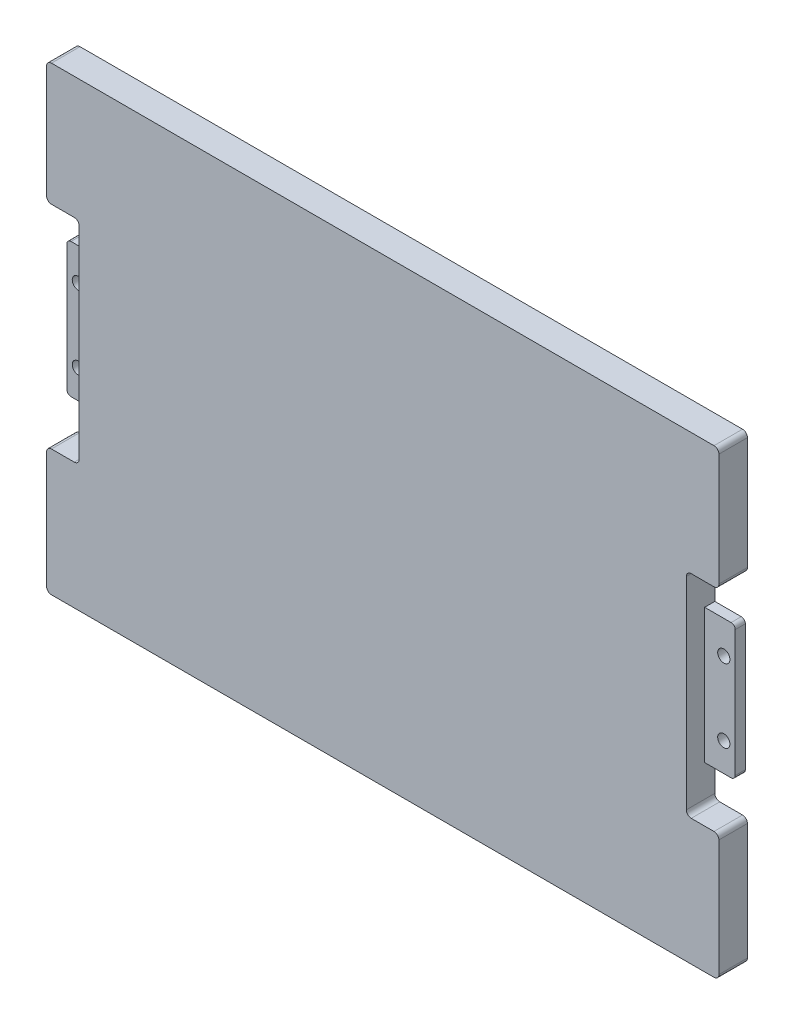
SolidWorks part; units mm, degrees
material "PBTP"
ref_plane "Front" through (0, 0, 0) normal (0, 0, 1) x (1, 0, 0)
ref_plane "Top" through (0, 0, 0) normal (0, 1, 0) x (1, 0, 0)
ref_plane "Right" through (0, 0, 0) normal (1, 0, 0) x (0, 0, -1)
sketch "Эскиз1" plane through (0, 0, 0) normal (0, 0, 1) x (1, 0, 0)
  line L0 (1.2018, 83) -> (6.7982, 83)
  line L1 (1.2018, 0) -> (163.7982, 0)
  line L2 (0, 1.2018) -> (0, 29.7982)
  line L3 (1.2018, 113) -> (163.7982, 113)
  line L4 (165, 1.2018) -> (165, 29.7982)
  line L5 (8, 81.7982) -> (8, 32.2018)
  line L6 (6.7982, 31) -> (1.2018, 31)
  line L7 (0, 84.2018) -> (0, 111.7982)
  line L8 (158.2018, 83) -> (163.7982, 83)
  line L9 (158.2018, 31) -> (163.7982, 31)
  line L10 (157, 81.7982) -> (157, 32.2018)
  line L11 (165, 84.2018) -> (165, 111.7982)
  arc A0 (0, 111.7982) -> (1.2018, 113) centre (1.2018, 111.7982) cw
  arc A1 (6.7982, 83) -> (8, 81.7982) centre (6.7982, 81.7982) cw
  arc A2 (1.2018, 83) -> (0, 84.2018) centre (1.2018, 84.2018) cw
  arc A3 (8, 32.2018) -> (6.7982, 31) centre (6.7982, 32.2018) cw
  arc A4 (1.2018, 31) -> (0, 29.7982) centre (1.2018, 29.7982) ccw
  arc A5 (1.2018, 0) -> (0, 1.2018) centre (1.2018, 1.2018) cw
  arc A6 (163.7982, 0) -> (165, 1.2018) centre (163.7982, 1.2018) ccw
  arc A7 (157, 32.2018) -> (158.2018, 31) centre (158.2018, 32.2018) ccw
  arc A8 (163.7982, 31) -> (165, 29.7982) centre (163.7982, 29.7982) cw
  arc A9 (158.2018, 83) -> (157, 81.7982) centre (158.2018, 81.7982) ccw
  arc A10 (163.7982, 83) -> (165, 84.2018) centre (163.7982, 84.2018) ccw
  arc A11 (163.7982, 113) -> (165, 111.7982) centre (163.7982, 111.7982) cw
  point P15 (0, 113)
  point P18 (8, 83)
  point P21 (0, 83)
  point P24 (8, 31)
  point P29 (0, 0)
  point P32 (165, 0)
  point P41 (165, 83)
  dimension "D9" = 1.2018
  dimension "D1" = 113
  dimension "D2" = 165
  dimension "D3" = 30
  dimension "D4" = 31
  dimension "D5" = 8
  dimension "D6" = 8
  dimension "D7" = 30
  dimension "D8" = 31
extrude "Бобышка-Вытянуть1" add sketch "Эскиз1" along normal blind 7
sketch "Эскиз2" plane through (0, 0, 0) normal (0, 0, -1) x (-1, 0, 0)
  line L0 (-163.7982, 113) -> (-1.2018, 113) construction
  line L1 (-161.7982, 111) -> (-3.2018, 111)
  line L2 (-163, 109.7982) -> (-163, 86.2018)
  line L3 (-161.7982, 2) -> (-3.2018, 2)
  line L4 (-2, 109.7982) -> (-2, 86.2018)
  line L5 (-1.2018, 0) -> (-163.7982, 0) construction
  line L6 (-165, 1.2018) -> (-165, 29.7982) construction
  line L7 (0, 111.7982) -> (0, 84.2018) construction
  line L8 (-161.7982, 85) -> (-156.2018, 85)
  line L9 (-155, 83.7982) -> (-155, 74.8)
  line L10 (-156.2018, 29) -> (-161.7982, 29)
  line L11 (-163, 27.7982) -> (-163, 3.2018)
  line L12 (-158.2018, 83) -> (-163.7982, 83) construction
  line L13 (-157, 32.2018) -> (-157, 81.7982) construction
  line L14 (-163.7982, 31) -> (-158.2018, 31) construction
  line L15 (-3.2018, 85) -> (-8.7982, 85)
  line L16 (-10, 83.7982) -> (-10, 30.2018)
  line L17 (-8.7982, 29) -> (-3.2018, 29)
  line L18 (-8, 81.7982) -> (-8, 32.2018) construction
  line L19 (-6.7982, 31) -> (-1.2018, 31) construction
  line L20 (-2, 27.7982) -> (-2, 3.2018)
  line L21 (-155, 74.8) -> (-155, 70.5)
  line L25 (-155, 70.5) -> (-155, 30.2018)
  circle A0 centre (-82.5, 57) radius 6
  arc A1 (-161.7982, 85) -> (-163, 86.2018) centre (-161.7982, 86.2018) cw
  arc A2 (-156.2018, 85) -> (-155, 83.7982) centre (-156.2018, 83.7982) cw
  arc A3 (-155, 30.2018) -> (-156.2018, 29) centre (-156.2018, 30.2018) cw
  arc A4 (-161.7982, 29) -> (-163, 27.7982) centre (-161.7982, 27.7982) ccw
  arc A5 (-163, 3.2018) -> (-161.7982, 2) centre (-161.7982, 3.2018) ccw
  arc A6 (-3.2018, 2) -> (-2, 3.2018) centre (-3.2018, 3.2018) ccw
  arc A7 (-3.2018, 29) -> (-2, 27.7982) centre (-3.2018, 27.7982) cw
  arc A8 (-10, 30.2018) -> (-8.7982, 29) centre (-8.7982, 30.2018) ccw
  arc A9 (-8.7982, 85) -> (-10, 83.7982) centre (-8.7982, 83.7982) ccw
  arc A10 (-3.2018, 85) -> (-2, 86.2018) centre (-3.2018, 86.2018) ccw
  arc A11 (-3.2018, 111) -> (-2, 109.7982) centre (-3.2018, 109.7982) cw
  arc A12 (-161.7982, 111) -> (-163, 109.7982) centre (-161.7982, 109.7982) ccw
  point P18 (-161, 83)
  point P31 (-4, 31)
  point P32 (-6, 29)
  point P45 (-155, 85)
  point P50 (-163, 29)
  point P57 (-2, 29)
  dimension "D12" = 12
  dimension "D17" = 1.2018
  dimension "D1" = 2
  dimension "D2" = 2
  dimension "D3" = 2
  dimension "D4" = 2
  dimension "D5" = 2
  dimension "D6" = 2
  dimension "D7" = 2
  dimension "D8" = 2
  dimension "D9" = 2
  dimension "D10" = 2
  dimension "D11" = 56
  dimension "D13" = 82.5
extrude "Вырез-Вытянуть1" cut sketch "Эскиз2" against normal blind 5
sketch "Эскиз3" plane through (0, 0, 5) normal (0, 0, -1) x (-1, 0, 0)
  line L0 (-1.2018, 0) -> (-163.7982, 0) construction
  line L1 (-120, 31) -> (-103, 31)
  line L2 (-121, 30) -> (-121, 19)
  line L3 (-120, 18) -> (-103, 18)
  line L4 (-102, 30) -> (-102, 19)
  line L5 (-165, 1.2018) -> (-165, 29.7982) construction
  line L6 (-41.4032, 94.6438) -> (-44.49, 94.6438)
  line L7 (-52.1501, 97.2393) -> (-39.1501, 97.2393)
  line L8 (-53.1501, 96.2393) -> (-53.1501, 83.2393)
  line L9 (-52.1501, 82.2393) -> (-39.1501, 82.2393)
  line L10 (-38.1501, 96.2393) -> (-38.1501, 83.2393)
  line L11 (-44.49, 94.6438) -> (-48.7847, 93.6372)
  line L12 (-48.7847, 93.6372) -> (-48.7847, 92.6306)
  line L13 (-48.7847, 92.6306) -> (-44.49, 93.6372)
  line L14 (-44.49, 93.6372) -> (-41.4032, 93.6372)
  line L15 (-41.4032, 93.6372) -> (-41.4032, 94.6438)
  line L16 (-48.7847, 91.7748) -> (-44.49, 92.6306)
  line L17 (-44.49, 92.6306) -> (-44.49, 91.7748)
  line L18 (-44.49, 91.7748) -> (-48.7847, 90.919)
  line L19 (-48.7847, 90.919) -> (-48.7847, 91.7748)
  line L20 (-48.7847, 90.0551) -> (-44.49, 90.9109)
  line L21 (-44.49, 90.9109) -> (-44.49, 90.0551)
  line L22 (-44.49, 90.0551) -> (-48.7847, 89.0679)
  line L23 (-48.7847, 90.0551) -> (-48.7847, 89.0679)
  line L24 (-48.7847, 88.2165) -> (-44.49, 89.0679)
  line L25 (-44.49, 89.0679) -> (-41.4032, 89.0679)
  line L26 (-41.4032, 89.0679) -> (-41.4032, 88.3169)
  line L27 (-41.4032, 88.3169) -> (-44.3412, 88.3169)
  line L28 (-44.3412, 88.3169) -> (-48.7847, 87.436)
  line L29 (-48.7847, 87.436) -> (-48.7847, 88.2165)
  line L30 (-48.6096, 93.8881) -> (-44.8588, 94.806)
  line L31 (-44.8588, 94.806) -> (-44.8588, 95.9138)
  line L32 (-44.8588, 95.9138) -> (-46.7342, 95.17)
  line L33 (-46.7342, 95.17) -> (-48.6096, 95.7398)
  line L34 (-48.6096, 95.7398) -> (-48.6096, 93.8881)
  line L35 (-48.6096, 87.0068) -> (-44.8588, 87.7157)
  line L36 (-44.8588, 87.7157) -> (-44.8588, 86.3281)
  line L37 (-44.8588, 86.3281) -> (-46.7342, 86.675)
  line L38 (-46.7342, 86.675) -> (-48.6096, 85.77)
  line L39 (-48.6096, 85.77) -> (-48.6096, 87.0068)
  arc A0 (-103, 18) -> (-102, 19) centre (-103, 19) ccw
  arc A1 (-121, 19) -> (-120, 18) centre (-120, 19) ccw
  arc A2 (-103, 31) -> (-102, 30) centre (-103, 30) cw
  arc A3 (-120, 31) -> (-121, 30) centre (-120, 30) ccw
  arc A4 (-39.1501, 97.2393) -> (-38.1501, 96.2393) centre (-39.1501, 96.2393) cw
  arc A5 (-39.1501, 82.2393) -> (-38.1501, 83.2393) centre (-39.1501, 83.2393) ccw
  arc A6 (-53.1501, 83.2393) -> (-52.1501, 82.2393) centre (-52.1501, 83.2393) ccw
  arc A7 (-52.1501, 97.2393) -> (-53.1501, 96.2393) centre (-52.1501, 96.2393) ccw
  point P10 (-102, 18)
  point P13 (-121, 18)
  point P16 (-102, 31)
  point P25 (-38.1501, 97.2393)
  point P30 (-53.1501, 82.2393)
  point P33 (-53.1501, 97.2393)
  dimension "D7" = 1
  dimension "D10" = 1
  dimension "D1" = 13
  dimension "D2" = 19
  dimension "D3" = 18
  dimension "D4" = 31
  dimension "D5" = 44
  dimension "D6" = 63
  dimension "D8" = 15
  dimension "D9" = 15
extrude "Вырез-Вытянуть2" cut sketch "Эскиз3" against normal blind 0.5
sketch "Эскиз4" plane through (0, 0, 0) normal (0, 0, -1) x (-1, 0, 0)
  line L0 (-163.5, 73) -> (-157, 73)
  line L1 (-157, 32.2018) -> (-157, 81.7982) construction
  line L2 (-164.5, 72) -> (-164.5, 41)
  line L3 (-163.5, 40) -> (-157, 40)
  line L4 (-163.7982, 113) -> (-1.2018, 113) construction
  line L5 (-1.2018, 0) -> (-163.7982, 0) construction
  line L6 (-8, 73) -> (-1.5, 73)
  line L7 (-8, 81.7982) -> (-8, 32.2018) construction
  line L8 (-0.5, 72) -> (-0.5, 41)
  line L9 (-1.5, 40) -> (-8, 40)
  line L10 (-8, 73) -> (-8, 40)
  line L18 (0, 1.2018) -> (0, 29.7982)
  line L19 (-1.2018, 31) -> (-6.7982, 31)
  line L20 (-8, 32.2018) -> (-8, 81.7982)
  line L21 (-6.7982, 83) -> (-1.2018, 83)
  line L22 (0, 84.2018) -> (0, 111.7982)
  line L23 (-1.2018, 113) -> (-163.7982, 113)
  line L24 (-165, 111.7982) -> (-165, 84.2018)
  line L25 (-163.7982, 83) -> (-158.2018, 83)
  line L26 (-157, 81.7982) -> (-157, 32.2018)
  line L27 (-158.2018, 31) -> (-163.7982, 31)
  line L28 (-165, 29.7982) -> (-165, 1.2018)
  line L29 (-163.7982, 0) -> (-1.2018, 0)
  line L38 (-157, 73) -> (-157, 40)
  circle A0 centre (-161.7, 65) radius 1.5
  circle A1 centre (-161.7, 47) radius 1.5
  circle A2 centre (-3.3, 65) radius 1.5
  circle A3 centre (-3.3, 47) radius 1.5
  arc A4 (-0.5, 41) -> (-1.5, 40) centre (-1.5, 41) cw
  arc A5 (-164.5, 41) -> (-163.5, 40) centre (-163.5, 41) ccw
  arc A6 (-163.5, 73) -> (-164.5, 72) centre (-163.5, 72) ccw
  arc A7 (-1.5, 73) -> (-0.5, 72) centre (-1.5, 72) cw
  arc A16 (0, 111.7982) -> (-1.2018, 113) centre (-1.2018, 111.7982) ccw
  arc A17 (0, 111.7982) -> (-1.2018, 113) centre (-1.2018, 111.7982) ccw
  arc A18 (-163.7982, 113) -> (-165, 111.7982) centre (-163.7982, 111.7982) ccw
  arc A19 (-163.7982, 113) -> (-165, 111.7982) centre (-163.7982, 111.7982) ccw
  arc A20 (-165, 84.2018) -> (-163.7982, 83) centre (-163.7982, 84.2018) ccw
  arc A21 (-165, 84.2018) -> (-163.7982, 83) centre (-163.7982, 84.2018) ccw
  arc A22 (-157, 81.7982) -> (-158.2018, 83) centre (-158.2018, 81.7982) ccw
  arc A23 (-157, 81.7982) -> (-158.2018, 83) centre (-158.2018, 81.7982) ccw
  arc A24 (-158.2018, 31) -> (-157, 32.2018) centre (-158.2018, 32.2018) ccw
  arc A25 (-158.2018, 31) -> (-157, 32.2018) centre (-158.2018, 32.2018) ccw
  arc A26 (-163.7982, 31) -> (-165, 29.7982) centre (-163.7982, 29.7982) ccw
  arc A27 (-163.7982, 31) -> (-165, 29.7982) centre (-163.7982, 29.7982) ccw
  arc A28 (-165, 1.2018) -> (-163.7982, 0) centre (-163.7982, 1.2018) ccw
  arc A29 (-165, 1.2018) -> (-163.7982, 0) centre (-163.7982, 1.2018) ccw
  arc A30 (-1.2018, 0) -> (0, 1.2018) centre (-1.2018, 1.2018) ccw
  arc A31 (-1.2018, 0) -> (0, 1.2018) centre (-1.2018, 1.2018) ccw
  arc A32 (0, 29.7982) -> (-1.2018, 31) centre (-1.2018, 29.7982) ccw
  arc A33 (0, 29.7982) -> (-1.2018, 31) centre (-1.2018, 29.7982) ccw
  arc A34 (-8, 32.2018) -> (-6.7982, 31) centre (-6.7982, 32.2018) ccw
  arc A35 (-8, 32.2018) -> (-6.7982, 31) centre (-6.7982, 32.2018) ccw
  arc A36 (-6.7982, 83) -> (-8, 81.7982) centre (-6.7982, 81.7982) ccw
  arc A37 (-6.7982, 83) -> (-8, 81.7982) centre (-6.7982, 81.7982) ccw
  arc A38 (-1.2018, 83) -> (0, 84.2018) centre (-1.2018, 84.2018) ccw
  arc A39 (-1.2018, 83) -> (0, 84.2018) centre (-1.2018, 84.2018) ccw
  dimension "D8" = 48
  dimension "D9" = 18
  dimension "D15" = 3
  dimension "D16" = 3
  dimension "D17" = 3
  dimension "D18" = 3
  dimension "D21" = 1
  dimension "D22" = 1
  dimension "D1" = 7.5
  dimension "D2" = 40
  dimension "D3" = 40
  dimension "D5" = 7.5
  dimension "D6" = 40
  dimension "D7" = 40
  dimension "D10" = 2.8
  dimension "D11" = 2.8
  dimension "D12" = 2.8
  dimension "D13" = 48
  dimension "D14" = 66
  dimension "D19" = 158.4
  dimension "D20" = 2.8
  dimension "D4" = 0
fillet "Скругление1" radius 1 24 edges at (155, 57, 5) (155.352, 29.352, 5) (159, 29, 5) (162.648, 28.648, 5) (163, 15.5, 5) (162.648, 2.352, 5) (82.5, 2, 5) (2.352, 2.352, 5) (2, 15.5, 5) (2.352, 28.648, 5) (6, 29, 5) (9.648, 29.352, 5) (10, 57, 5) (9.648, 84.648, 5) (6, 85, 5) (2.352, 85.352, 5) (2, 98, 5) (2.352, 110.648, 5) (155.352, 84.648, 5) (159, 85, 5) (162.648, 85.352, 5) (163, 98, 5) (162.648, 110.648, 5) (82.5, 111, 5)
extrude "Бобышка-Вытянуть3" add sketch "Эскиз4" against normal blind 2.5 contours L6 L10 L9 L8 A3 A2 | L38 L0 L2 L3 A1 A0
sketch "Эскиз5" plane through (0, 0, 0) normal (0, 0, -1) x (-1, 0, 0)
  line L0 (-155, 30.2018) -> (-155, 83.7982) construction
  line L1 (-155, 70.5) -> (-156.5, 70.5)
  line L2 (-155, 70.5) -> (-155, 74.8)
  line L3 (-155, 74.8) -> (-156.5, 74.8)
  line L4 (-156.5, 70.5) -> (-156.5, 74.8)
  line L5 (-165, 84.2018) -> (-165, 111.7982) construction
  line L6 (-163.7982, 113) -> (-1.2018, 113) construction
  point P8 (-156.5, 72.65)
  dimension "D1" = 8.5
  dimension "D2" = 42.5
  dimension "D3" = 38.2
extrude "Вырез-Вытянуть3" cut sketch "Эскиз5" against normal blind 2.5
sketch "Эскиз6" plane through (0, 0, 0) normal (0, 0, -1) x (-1, 0, 0)
  line L0 (-155, 83.7982) -> (-155, 74.8) construction
  line L1 (-155, 83) -> (-158.1743, 83)
  line L2 (-155, 83) -> (-155, 80)
  line L3 (-155, 80) -> (-158.1743, 80)
  line L4 (-158.1743, 83) -> (-158.1743, 80)
  line L5 (-163.7982, 113) -> (-1.2018, 113) construction
  point P8 (-156.5871, 83)
  dimension "D1" = 30
  dimension "D2" = 33
extrude "Вырез-Вытянуть4" cut sketch "Эскиз6" against normal blind 1
